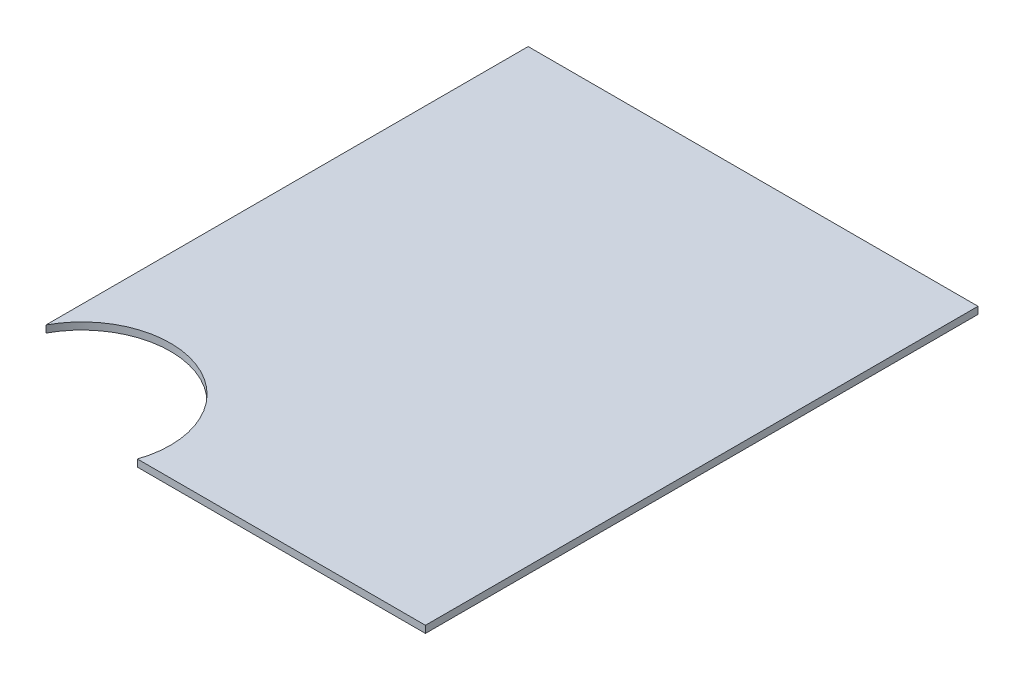
SolidWorks part; units mm, degrees
ref_plane "Front Plane" through (0, 0, 0) normal (0, 0, 1) x (1, 0, 0)
ref_plane "Top Plane" through (0, 0, 0) normal (0, 1, 0) x (1, 0, 0)
ref_plane "Right Plane" through (0, 0, 0) normal (1, 0, 0) x (0, 0, -1)
sketch "Sketch1" plane through (0, 0, 0) normal (0, 1, 0) x (1, 0, 0)
  line L1 (63.5, -78) -> (-63.5, -78)
  line L2 (63.5, -78) -> (63.5, 78)
  line L3 (63.5, 78) -> (-63.5, 78)
  line L4 (-63.5, -78) -> (-63.5, 78)
  line L5 (63.5, -78) -> (-63.5, 78) construction
  line L6 (63.5, 78) -> (-63.5, -78) construction
  point P0 (0, 0)
  dimension "D1" = 156
  dimension "D2" = 127
extrude "Boss-Extrude1" add sketch "Sketch1" along normal blind 2
ref_plane "Plane1" through (0, 2, 0) normal (0, 1, 0) x (1, 0, 0)
sketch "Sketch2" plane through (0, 2, 0) normal (0, 1, 0) x (1, 0, 0)
  line L0 (-63.5, -78) -> (-41.5, -78) construction
  line L2 (-63.5, -78) -> (63.5, -78) construction
  line L6 (-41.5, -78) -> (-41.5, -70) construction
  circle A1 centre (-41.5, -70) radius 25
  dimension "D3" = 50
  dimension "D1" = 22
  dimension "D2" = 8
extrude "Cut-Extrude1" cut sketch "Sketch2" against normal blind 2
